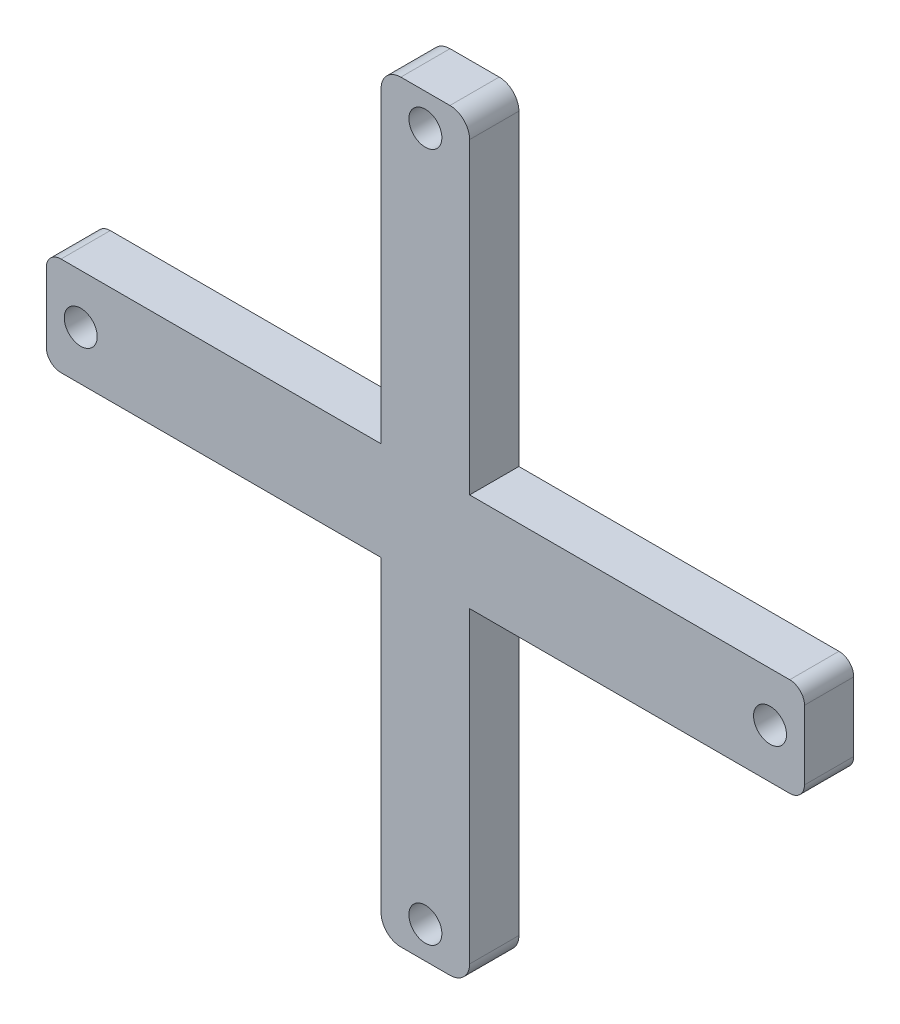
SolidWorks part; units mm, degrees
ref_plane "Front Plane" through (0, 0, 0) normal (0, 0, 1) x (1, 0, 0)
ref_plane "Top Plane" through (0, 0, 0) normal (0, 1, 0) x (1, 0, 0)
ref_plane "Right Plane" through (0, 0, 0) normal (1, 0, 0) x (0, 0, -1)
sketch "Sketch1" plane through (0, 0, 0) normal (0, 0, 1) x (1, 0, 0)
  line L1 (93.98, -12.7) -> (-93.98, -12.7)
  line L2 (97.79, -8.89) -> (97.79, 8.89)
  line L3 (93.98, 12.7) -> (-93.98, 12.7)
  line L4 (-97.79, -8.89) -> (-97.79, 8.89)
  line L5 (97.79, -12.7) -> (-97.79, 12.7) construction
  line L6 (97.79, 12.7) -> (-97.79, -12.7) construction
  arc A0 (97.79, 8.89) -> (93.98, 12.7) centre (93.98, 8.89) ccw
  arc A1 (93.98, -12.7) -> (97.79, -8.89) centre (93.98, -8.89) ccw
  arc A2 (-93.98, -12.7) -> (-97.79, -8.89) centre (-93.98, -8.89) cw
  arc A3 (-93.98, 12.7) -> (-97.79, 8.89) centre (-93.98, 8.89) ccw
  circle A4 centre (-88.9, 0) radius 4.25
  circle A5 centre (88.9, 0) radius 4.25
  point P0 (0, 0)
  dimension "D3" = 3.81
  dimension "D6" = 8.5
  dimension "D7" = 8.5
  dimension "D1" = 25.4
  dimension "D2" = 195.58
  dimension "D4" = 88.9
  dimension "D5" = 88.9
extrude "Boss-Extrude1" add sketch "Sketch1" along normal blind 12.7
sketch "Sketch3" plane through (0, 0, 12.7) normal (0, 0, 1) x (1, 0, 0)
  line L1 (-6.3354, -97.155) -> (6.3354, -97.155)
  line L2 (-11.4154, -92.075) -> (-11.4154, 92.075)
  line L3 (-6.3354, 97.155) -> (6.3354, 97.155)
  line L4 (11.4154, -92.075) -> (11.4154, 92.075)
  line L5 (-11.4154, -97.155) -> (11.4154, 97.155) construction
  line L6 (-11.4154, 97.155) -> (11.4154, -97.155) construction
  arc A0 (-6.3354, -97.155) -> (-11.4154, -92.075) centre (-6.3354, -92.075) cw
  arc A1 (6.3354, -97.155) -> (11.4154, -92.075) centre (6.3354, -92.075) ccw
  arc A2 (-11.4154, 92.075) -> (-6.3354, 97.155) centre (-6.3354, 92.075) cw
  arc A3 (6.3354, 97.155) -> (11.4154, 92.075) centre (6.3354, 92.075) cw
  circle A4 centre (0, 88.9) radius 4.25
  circle A5 centre (0, -88.9) radius 4.25
  point P0 (0, 0)
  dimension "D1" = 5.08
  dimension "D3" = 88.9
  dimension "D5" = 8.5
  dimension "D6" = 8.5
  dimension "D2" = 88.9
  dimension "D4" = 184.15
extrude "Boss-Extrude3" add sketch "Sketch3" against normal through all
sketch "Sketch2" plane through (0, 0, 0) normal (0, 0, -1) x (-1, 0, 0)
  circle A4 centre (0, 88.9) radius 4.25
  circle A5 centre (-88.9, 0) radius 4.25
  circle A6 centre (0, -88.9) radius 4.25
  circle A7 centre (88.9, 0) radius 4.25
extrude "Boss-Extrude2" add sketch "Sketch2" against normal blind 6.35
